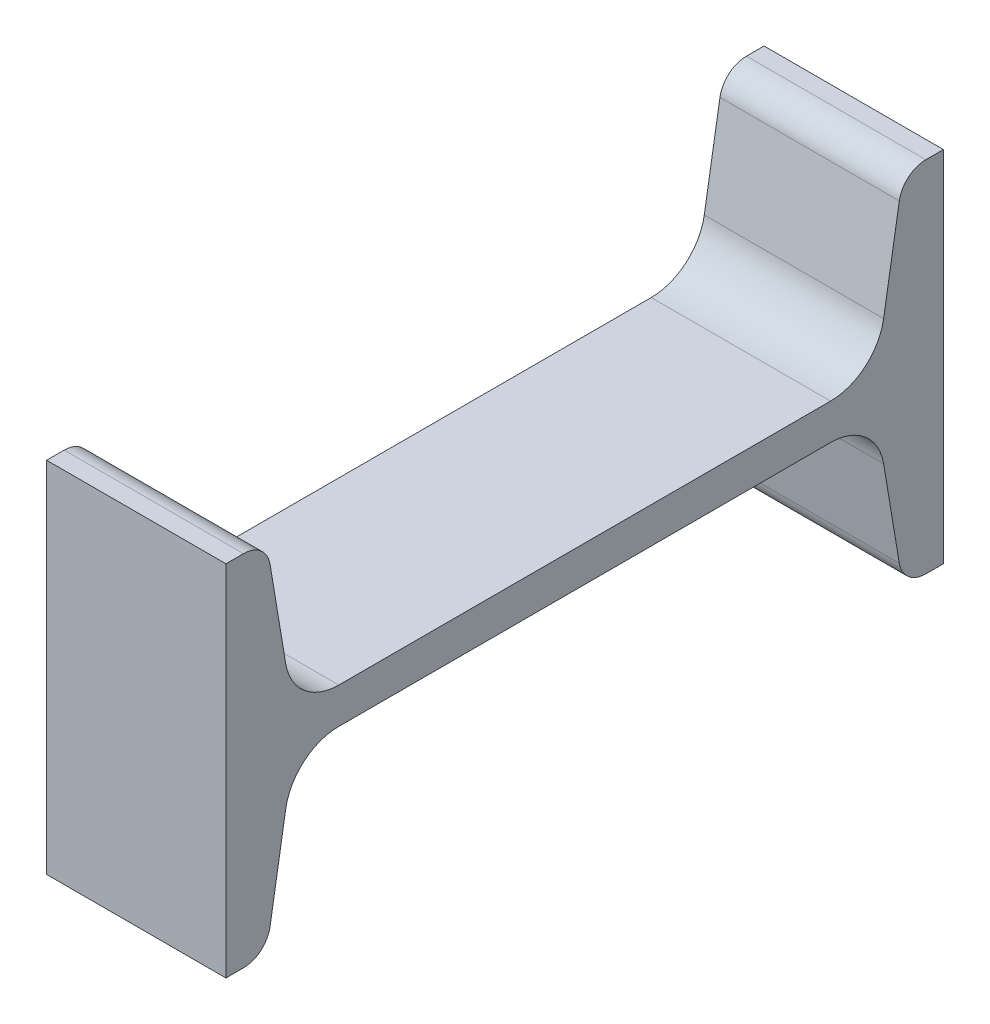
SolidWorks part; units mm, degrees
ref_plane "Ön Düzlem" through (0, 0, 0) normal (0, 0, 1) x (1, 0, 0)
ref_plane "Üst Düzlem" through (0, 0, 0) normal (0, 1, 0) x (1, 0, 0)
ref_plane "Sağ Düzlem" through (0, 0, 0) normal (1, 0, 0) x (0, 0, -1)
sketch "Çizim1" plane through (0, 0, 0) normal (0, 0, 1) x (1, 0, 0)
  line L0 (0, 0) -> (20, 0)
  dimension "D1" = 20
other "Sb kiriş 80 X 6(1)"
ref_plane "Düzlem2" through (0, 0, 0) normal (1, 0, 0) x (0, 1, 0)
sketch "Sketch1" plane through (0, 0, 0) normal (1, 0, 0) x (0, 1, 0)
  line L0 (-20, -40) -> (-20, -38.0415)
  line L1 (-17.4932, -35.0823) -> (-7.0135, -33.3355)
  line L2 (-2, -27.4172) -> (-2, 27.4172)
  line L3 (-7.0135, 33.3355) -> (-17.4932, 35.0823)
  line L4 (-20, 38.0415) -> (-20, 40)
  line L5 (-20, 40) -> (20, 40)
  line L6 (20, 40) -> (20, 38.0415)
  line L7 (17.4932, 35.0823) -> (7.0135, 33.3355)
  line L8 (2, 27.4172) -> (2, -27.4172)
  line L9 (7.0135, -33.3355) -> (17.4932, -35.0823)
  line L10 (20, -38.0415) -> (20, -40)
  line L11 (20, -40) -> (-20, -40)
  line L15 (-2, 0) -> (2, 0) construction
  arc A0 (-7.0135, -33.3355) -> (-2, -27.4172) centre (-8, -27.4172) ccw
  arc A1 (-2, 27.4172) -> (-7.0135, 33.3355) centre (-8, 27.4172) ccw
  arc A2 (7.0135, 33.3355) -> (2, 27.4172) centre (8, 27.4172) ccw
  arc A3 (2, -27.4172) -> (7.0135, -33.3355) centre (8, -27.4172) ccw
  arc A4 (-17.4932, 35.0823) -> (-20, 38.0415) centre (-17, 38.0415) cw
  arc A5 (17.4932, 35.0823) -> (20, 38.0415) centre (17, 38.0415) ccw
  arc A6 (-20, -38.0415) -> (-17.4932, -35.0823) centre (-17, -38.0415) cw
  arc A7 (20, -38.0415) -> (17.4932, -35.0823) centre (17, -38.0415) ccw
  point P1 (0, 40)
  point P8 (0, -40)
  point P21 (0, 0)
  point P34 (0, 0)
  dimension "RI" = 6
  dimension "D3" = 3
  dimension "BF" = 40
  dimension "D2" = 9.463
  dimension "DEPTH" = 80
  dimension "TW" = 4
  dimension "D1" = 54.8344
